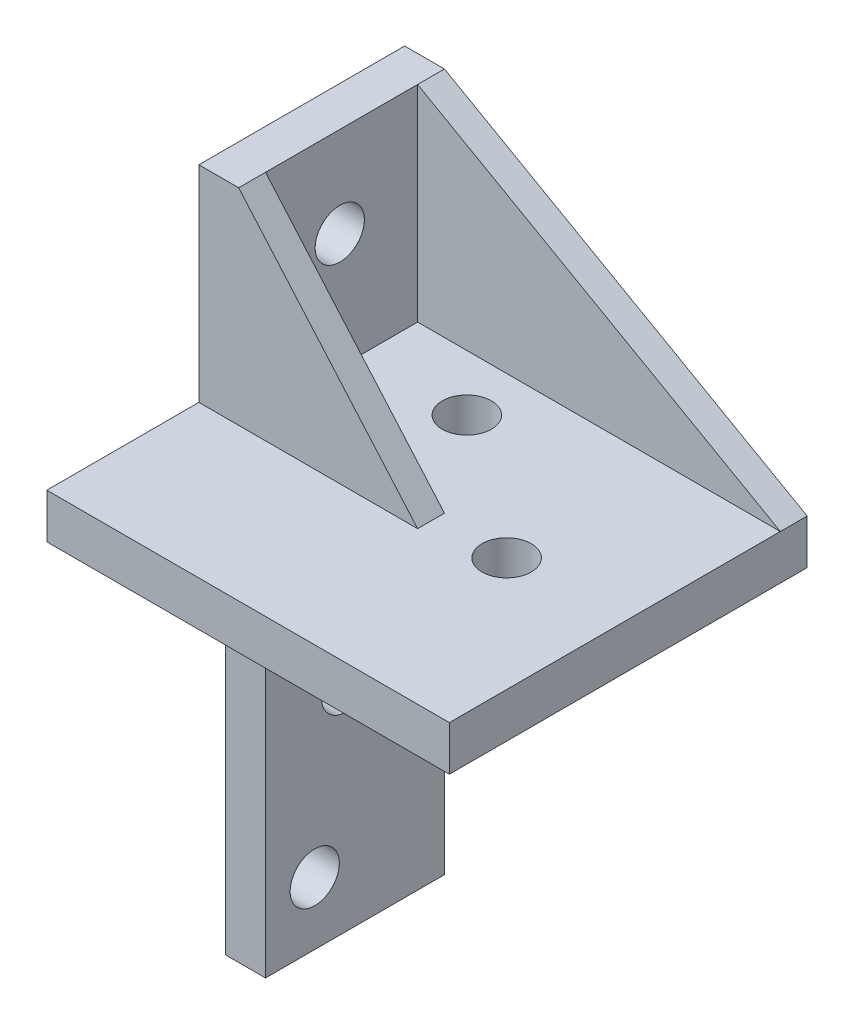
SolidWorks part; units mm, degrees
ref_plane "Front Plane" through (0, 0, 0) normal (0, 0, 1) x (1, 0, 0)
ref_plane "Top Plane" through (0, 0, 0) normal (0, 1, 0) x (1, 0, 0)
ref_plane "Right Plane" through (0, 0, 0) normal (1, 0, 0) x (0, 0, -1)
sketch "Sketch1" plane through (0, 0, 0) normal (1, 0, 0) x (0, 0, -1)
  line L1 (0, 0) -> (20, 0)
  line L2 (0, 0) -> (0, 50)
  line L3 (0, 50) -> (20, 50)
  line L4 (20, 0) -> (20, 50)
  dimension "D1" = 20
  dimension "D2" = 50
extrude "Boss-Extrude1" add sketch "Sketch1" along normal blind 4.45
sketch "Sketch2" plane through (0, 50, 0) normal (0, 1, 0) x (1, 0, 0)
  line L1 (0, 20) -> (45, 20)
  line L2 (0, 20) -> (0, -20)
  line L3 (0, -20) -> (45, -20)
  line L4 (45, 20) -> (45, -20)
  dimension "D1" = 45
  dimension "D2" = 40
extrude "Boss-Extrude2" add sketch "Sketch2" along normal blind 5
sketch "Sketch4" plane through (0, 55, 0) normal (0, 1, 0) x (1, 0, 0)
  line L1 (45, -20) -> (45, 20) construction
  line L3 (0, 20) -> (0, -20) construction
  line L4 (45, 20) -> (0, 20) construction
  circle A0 centre (32.25, -0.85) radius 2.75
  circle A1 centre (16.2, 10.75) radius 2.75
  dimension "D1" = 5.5
  dimension "D2" = 10
  dimension "D3" = 20.85
  dimension "D4" = 16.2
  dimension "D5" = 9.25
extrude "Cut-Extrude1" cut sketch "Sketch4" against normal up to next
sketch "Sketch5" plane through (4.45, 0, 0) normal (1, 0, 0) x (0, 0, -1)
  line L0 (0, 50) -> (0, 0) construction
  line L1 (20, 50) -> (0, 50) construction
  line L3 (0, 0) -> (20, 0) construction
  circle A0 centre (9, 24) radius 2.75
  circle A1 centre (5.5, 7) radius 2.75
  dimension "D1" = 5.5
  dimension "D2" = 9
  dimension "D3" = 26
  dimension "D4" = 5.5
  dimension "D5" = 7
extrude "Cut-Extrude2" cut sketch "Sketch5" against normal through all
sketch "Sketch6" plane through (0, 55, 0) normal (0, 1, 0) x (1, 0, 0)
  line L1 (0, 20) -> (4.45, 20)
  line L2 (0, 20) -> (0, 0)
  line L3 (0, 0) -> (4.45, 0)
  line L4 (4.45, 20) -> (4.45, 0)
  dimension "D1" = 4.45
  dimension "D2" = 20
extrude "Boss-Extrude3" add sketch "Sketch6" along normal blind 23
sketch "Sketch7" plane through (4.45, 0, 0) normal (1, 0, 0) x (0, 0, -1)
  line L0 (0, 78) -> (0, 55) construction
  line L1 (0, 78) -> (20, 78) construction
  circle A0 centre (8.3, 67.9) radius 2.75
  dimension "D1" = 5.5
  dimension "D2" = 8.3
  dimension "D3" = 10.1
extrude "Cut-Extrude3" cut sketch "Sketch7" against normal through all
sketch "Sketch8" plane through (0, 0, -20) normal (0, 0, -1) x (-1, 0, 0)
  line L0 (-4.45, 78) -> (-4.45, 55)
  line L1 (-4.45, 55) -> (-45, 55)
  line L2 (-45, 55) -> (-4.45, 78)
extrude "Boss-Extrude4" add sketch "Sketch8" against normal blind 3
sketch "Sketch9" plane through (0, 0, 0) normal (0, 0, 1) x (1, 0, 0)
  line L1 (4.45, 55) -> (24.45, 55)
  line L2 (24.45, 55) -> (4.45, 78)
  line L3 (4.45, 78) -> (0, 78)
  line L4 (0, 78) -> (0, 55)
  line L5 (0, 55) -> (4.45, 55)
  dimension "D1" = 20
extrude "Boss-Extrude5" add sketch "Sketch9" along normal blind 3
